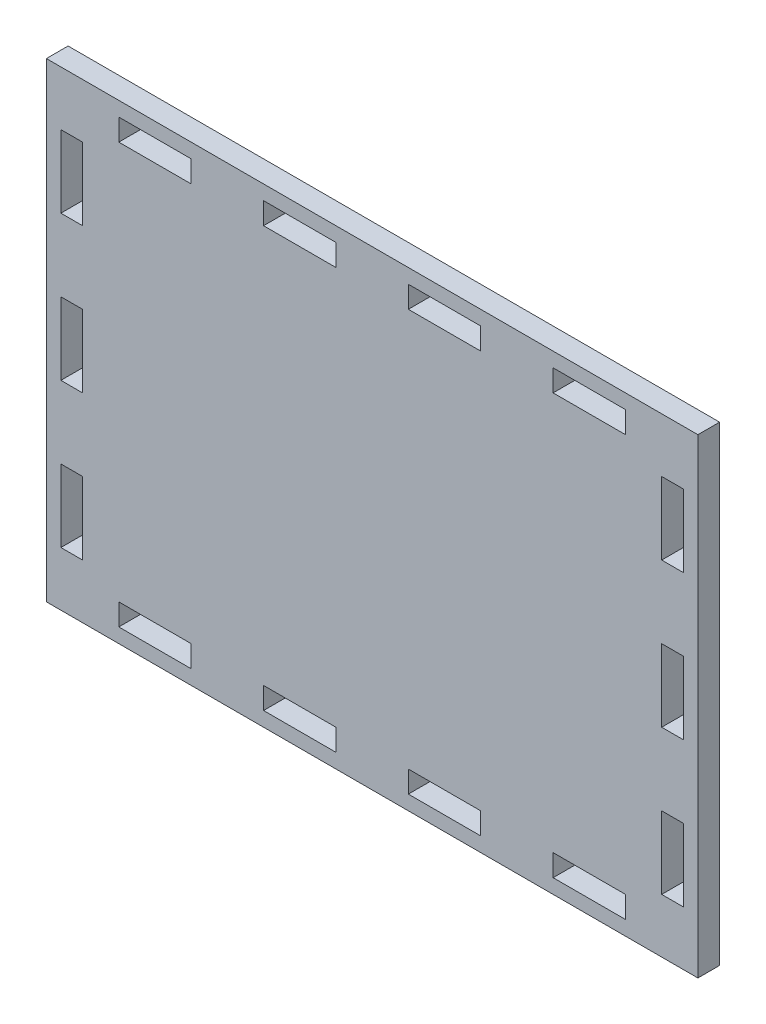
SolidWorks part; units mm, degrees
ref_plane "前视基准面" through (0, 0, 0) normal (0, 0, 1) x (1, 0, 0)
ref_plane "上视基准面" through (0, 0, 0) normal (0, 1, 0) x (1, 0, 0)
ref_plane "右视基准面" through (0, 0, 0) normal (1, 0, 0) x (0, 0, -1)
sketch "草图1" plane through (0, 0, 0) normal (0, 0, 1) x (1, 0, 0)
  line L0 (-15, 30.5) -> (-15, 27.5)
  line L1 (-45, 32.5) -> (45, 32.5)
  line L2 (-45, 32.5) -> (-45, -32.5)
  line L3 (-45, -32.5) -> (45, -32.5)
  line L4 (45, 32.5) -> (45, -32.5)
  line L5 (-45, 32.5) -> (45, -32.5) construction
  line L6 (-45, -32.5) -> (45, 32.5) construction
  line L7 (-35, 30.5) -> (-25, 30.5)
  line L8 (-35, 30.5) -> (-35, 27.5)
  line L9 (-35, 27.5) -> (-25, 27.5)
  line L10 (-25, 30.5) -> (-25, 27.5)
  line L11 (-43, 25) -> (-40, 25)
  line L12 (-43, 25) -> (-43, 15)
  line L13 (-43, 15) -> (-40, 15)
  line L14 (-40, 25) -> (-40, 15)
  line L15 (-15, 30.5) -> (-5, 30.5)
  line L16 (-5, 30.5) -> (-5, 27.5)
  line L17 (-15, 27.5) -> (-5, 27.5)
  line L18 (5, 30.5) -> (5, 27.5)
  line L19 (5, 30.5) -> (15, 30.5)
  line L20 (15, 30.5) -> (15, 27.5)
  line L21 (5, 27.5) -> (15, 27.5)
  line L22 (25, 30.5) -> (25, 27.5)
  line L23 (25, 30.5) -> (35, 30.5)
  line L24 (35, 30.5) -> (35, 27.5)
  line L25 (25, 27.5) -> (35, 27.5)
  line L26 (-43, 5) -> (-43, -5)
  line L27 (-43, 5) -> (-40, 5)
  line L28 (-40, 5) -> (-40, -5)
  line L29 (-43, -5) -> (-40, -5)
  line L30 (-43, -15) -> (-43, -25)
  line L31 (-43, -15) -> (-40, -15)
  line L32 (-40, -15) -> (-40, -25)
  line L33 (-43, -25) -> (-40, -25)
  line L34 (0, -55) -> (0, 55) construction
  line L35 (43, -15) -> (40, -15)
  line L36 (40, -15) -> (40, -25)
  line L37 (43, -25) -> (40, -25)
  line L38 (43, -15) -> (43, -25)
  line L39 (43, 5) -> (40, 5)
  line L40 (40, 5) -> (40, -5)
  line L41 (43, -5) -> (40, -5)
  line L42 (43, 5) -> (43, -5)
  line L43 (43, 15) -> (40, 15)
  line L44 (40, 25) -> (40, 15)
  line L45 (43, 25) -> (40, 25)
  line L46 (43, 25) -> (43, 15)
  line L47 (55, 0) -> (-55, 0) construction
  line L48 (25, -30.5) -> (35, -30.5)
  line L49 (35, -30.5) -> (35, -27.5)
  line L50 (25, -27.5) -> (35, -27.5)
  line L51 (25, -30.5) -> (25, -27.5)
  line L52 (5, -30.5) -> (15, -30.5)
  line L53 (15, -30.5) -> (15, -27.5)
  line L54 (5, -27.5) -> (15, -27.5)
  line L55 (5, -30.5) -> (5, -27.5)
  line L56 (-15, -30.5) -> (-5, -30.5)
  line L57 (-5, -30.5) -> (-5, -27.5)
  line L58 (-15, -27.5) -> (-5, -27.5)
  line L59 (-15, -30.5) -> (-15, -27.5)
  line L60 (-35, -27.5) -> (-25, -27.5)
  line L61 (-25, -30.5) -> (-25, -27.5)
  line L62 (-35, -30.5) -> (-25, -30.5)
  line L63 (-35, -30.5) -> (-35, -27.5)
  point P0 (0, 0)
  dimension "D1" = 90
  dimension "D2" = 65
  dimension "D3" = 10
  dimension "D4" = 3
  dimension "D5" = 10
  dimension "D6" = 3
  dimension "D7" = 10
  dimension "D8" = 2
  dimension "D9" = 2
  dimension "D10" = 7.5
  dimension "D11" = 4
  dimension "D12" = 3
extrude "凸台-拉伸1" add sketch "草图1" along normal blind 3
